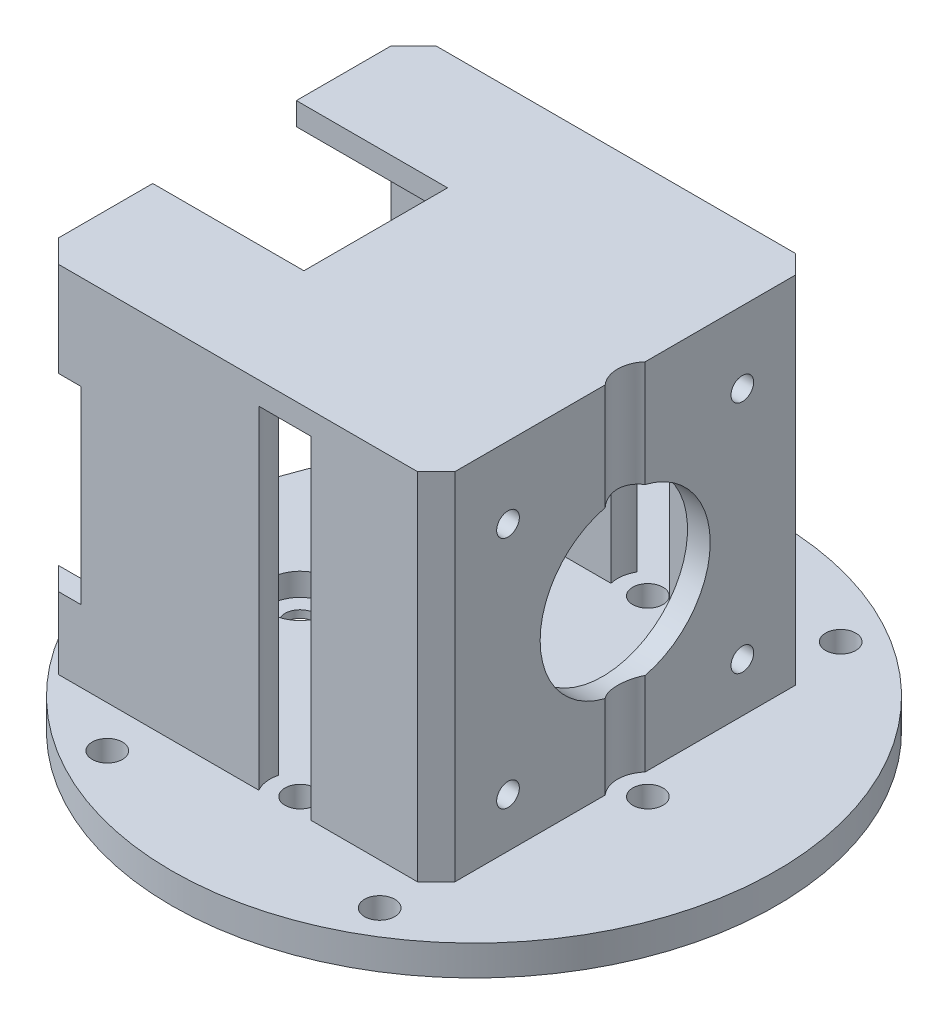
SolidWorks part; units mm, degrees
ref_plane "前视基准面" through (0, 0, 0) normal (0, 0, 1) x (1, 0, 0)
ref_plane "上视基准面" through (0, 0, 0) normal (0, 1, 0) x (1, 0, 0)
ref_plane "右视基准面" through (0, 0, 0) normal (1, 0, 0) x (0, 0, -1)
other "Configuration Table"
sketch "草图1" plane through (0, 0, 0) normal (0, 1, 0) x (1, 0, 0)
  circle A0 centre (0, 0) radius 40
  circle A1 centre (0, 0) radius 23 construction
  circle A2 centre (0, 23) radius 2
  circle A3 centre (23, 0) radius 2
  circle A4 centre (0, -23) radius 2
  circle A5 centre (-23, 0) radius 2
  point P15 (0, 0)
  dimension "D1" = 80
  dimension "D2" = 46
  dimension "D3" = 4
  dimension "D4" = 4
extrude "凸台-拉伸1" add sketch "草图1" along normal blind 4
sketch "草图2" plane through (0, 4, 0) normal (0, 1, 0) x (1, 0, 0)
  line L0 (-8, 0) -> (0, 0) construction
  line L1 (-33, 22) -> (-3.873, 22)
  line L3 (-33, -22) -> (-3.873, -22)
  line L4 (17, 22) -> (17, -22)
  line L5 (-33, 22) -> (17, -22) construction
  line L6 (-33, -22) -> (17, 22) construction
  line L7 (-33, -22) -> (-30, -25)
  line L8 (-30, -25) -> (-3.4641, -25)
  line L9 (-33, 22) -> (-30, 25)
  line L10 (17, -22) -> (3.873, -22) construction
  line L12 (-30, 25) -> (-3.4641, 25)
  line L14 (-33, 22) -> (-3.873, 22) construction
  line L15 (17.5251, 25) -> (20, 22.5251)
  line L16 (20, 22.5251) -> (20, 2.6458)
  line L17 (20, -22.5251) -> (17.5251, -25)
  line L18 (3.4641, 25) -> (17.5251, 25)
  line L19 (20, -2.6458) -> (20, -22.5251)
  line L20 (3.4641, -25) -> (17.5251, -25)
  line L21 (3.873, 22) -> (17, 22)
  line L22 (3.873, 22) -> (17, 22) construction
  line L23 (3.873, -22) -> (17, -22)
  line L24 (-3.873, -22) -> (-33, -22) construction
  circle A0 centre (-23, 0) radius 4
  arc A1 (20, 2.6458) -> (20, -2.6458) centre (23, 0) ccw
  arc A3 (3.4641, -25) -> (3.873, -22) centre (0, -23) ccw
  arc A4 (-3.4641, 25) -> (-3.873, 22) centre (0, 23) ccw
  arc A5 (3.873, 22) -> (3.4641, 25) centre (0, 23) ccw
  arc A6 (-3.873, -22) -> (-3.4641, -25) centre (0, -23) ccw
  circle A7 centre (23, 0) radius 4
  point P0 (-8, 0)
  dimension "D4" = 8
  dimension "D11" = 8
  dimension "D12" = 8
  dimension "D13" = 8
  dimension "D14" = 135
  dimension "D17" = 8
  dimension "D1" = 44
  dimension "D2" = 50
  dimension "D3" = 8
  dimension "D5" = 50
  dimension "D6" = 45
  dimension "D7" = 135
  dimension "D8" = 3
  dimension "D9" = 3
  dimension "D10" = 3
  dimension "D15" = 3.5
  dimension "D16" = 3.5
extrude "凸台-拉伸2" add sketch "草图2" along normal blind 44 contours L9 L12 A4 L1 | L4 L23 A3 L20 L17 L19 A1 L16 L15 L18 A5 L21 | L3 A6 L8 L7
sketch "草图3" plane through (0, 48, 0) normal (0, 1, 0) x (1, 0, 0)
  line L0 (-3.4641, 25) -> (3.4641, 25)
  line L1 (-3.873, 22) -> (3.873, 22) construction
  line L2 (-3.873, -22) -> (3.873, -22) construction
  line L3 (-33, 22) -> (-3.873, 22)
  line L4 (-3.4641, 25) -> (-30, 25)
  line L5 (-30, 25) -> (-33, 22)
  line L6 (-33, 22) -> (-3.873, 22) construction
  line L7 (-3.4641, 25) -> (-30, 25)
  line L8 (-30, 25) -> (-33, 22)
  line L9 (-33, -22) -> (-30, -25)
  line L10 (-30, -25) -> (-3.4641, -25)
  line L11 (-3.873, -22) -> (-33, -22)
  line L12 (-33, -22) -> (-30, -25)
  line L13 (-30, -25) -> (-3.4641, -25)
  line L14 (-3.873, -22) -> (-33, -22) construction
  line L15 (3.873, 22) -> (17, 22)
  line L16 (17, 22) -> (17, -22)
  line L17 (17, -22) -> (3.873, -22)
  line L18 (3.4641, -25) -> (17.5251, -25)
  line L19 (17.5251, -25) -> (20, -22.5251)
  line L20 (20, -22.5251) -> (20, -2.6458)
  line L21 (20, 2.6458) -> (20, 22.5251)
  line L22 (20, 22.5251) -> (17.5251, 25)
  line L23 (17.5251, 25) -> (3.4641, 25)
  line L24 (3.873, 22) -> (17, 22) construction
  line L25 (17, 22) -> (17, -22) construction
  line L26 (17, -22) -> (3.873, -22) construction
  line L27 (3.4641, -25) -> (17.5251, -25)
  line L28 (17.5251, -25) -> (20, -22.5251)
  line L29 (20, -22.5251) -> (20, -2.6458)
  line L30 (20, 2.6458) -> (20, 22.5251)
  line L31 (20, 22.5251) -> (17.5251, 25)
  line L32 (17.5251, 25) -> (3.4641, 25)
  line L33 (-3.4641, -25) -> (3.4641, -25)
  line L34 (-33, 22) -> (-33, 9.5)
  line L35 (17, 0) -> (-13, 0) construction
  line L36 (-13, 7.5) -> (-13, -7.5)
  line L39 (-33, -9.5) -> (-33, -22)
  line L40 (-13, 7.5) -> (-13, 9.5)
  line L41 (-13, 9.5) -> (-23, 9.5)
  line L43 (-13, -9.5) -> (-23, -9.5)
  line L46 (-13, -7.5) -> (-13, -9.5)
  line L47 (-23, 9.5) -> (-33, 9.5)
  line L48 (-33, -9.5) -> (-23, -9.5)
  arc A1 (-3.4641, 25) -> (-3.873, 22) centre (0, 23) ccw
  arc A3 (-3.873, -22) -> (-3.4641, -25) centre (0, -23) ccw
  arc A5 (3.4641, -25) -> (3.873, -22) centre (0, -23) ccw
  arc A6 (20, 2.6458) -> (20, -2.6458) centre (23, 0) ccw
  arc A7 (3.873, 22) -> (3.4641, 25) centre (0, 23) ccw
  arc A9 (20, 2.6458) -> (20, -2.6458) centre (23, 0) ccw
  dimension "D4" = 30
  dimension "D5" = 15
  dimension "D6" = 19
  dimension "D8" = 10
  dimension "D1" = 0
  dimension "D2" = 0
  dimension "D3" = 0
extrude "凸台-拉伸4" add sketch "草图3" along normal blind 3
sketch "草图5" plane through (17, 0, 0) normal (-1, 0, 0) x (0, 0, 1)
  line L0 (-22, 48) -> (22, 4) construction
  line L1 (22, 48) -> (-22, 4) construction
  line L3 (-15.5, 41.5) -> (15.5, 41.5) construction
  line L4 (-15.5, 41.5) -> (-15.5, 10.5) construction
  line L5 (-15.5, 10.5) -> (15.5, 10.5) construction
  line L6 (15.5, 41.5) -> (15.5, 10.5) construction
  line L7 (-15.5, 41.5) -> (15.5, 10.5) construction
  line L8 (-15.5, 10.5) -> (15.5, 41.5) construction
  circle A0 centre (15.5, 41.5) radius 1.5
  circle A1 centre (-15.5, 41.5) radius 1.5
  circle A2 centre (-15.5, 10.5) radius 1.5
  circle A3 centre (15.5, 10.5) radius 1.5
  circle A4 centre (0, 26) radius 11.25
  point P8 (0, 26)
  dimension "D3" = 3
  dimension "D6" = 22.5
  dimension "D1" = 31
  dimension "D2" = 31
  dimension "D4" = 2
  dimension "D5" = 2
extrude "切除-拉伸1" cut sketch "草图5" against normal through all
sketch "草图6" plane through (0, 0, 25) normal (0, 0, 1) x (1, 0, 0)
  line L0 (-33, 26) -> (20, 26) construction
  line L1 (-33, 48) -> (-33, 4) construction
  line L2 (20, 51) -> (20, 4) construction
  line L3 (-33, 38.5) -> (-33, 13.5)
  line L4 (-33, 38.5) -> (-27, 38.5)
  line L5 (-27, 38.5) -> (-27, 13.5)
  line L6 (-33, 13.5) -> (-27, 13.5)
  point P10 (-27, 26)
  dimension "D1" = 12.5
  dimension "D2" = 6
extrude "切除-拉伸2" cut sketch "草图6" against normal blind 3
sketch "草图8" plane through (0, 4, 0) normal (0, 1, 0) x (1, 0, 0)
  line L0 (0, 0) -> (23, 0) construction
  line L1 (0, 0) -> (18.0143, 30.4969) construction
  line L2 (0, 0) -> (0, 35.42) construction
  circle A0 centre (0, 0) radius 35.42 construction
  circle A1 centre (18.0143, 30.4969) radius 2
  circle A2 centre (18.0143, -30.4969) radius 2
  circle A3 centre (-18.0143, -30.4969) radius 2
  circle A4 centre (-18.0143, 30.4969) radius 2
  dimension "D1" = 70.84
  dimension "D3" = 4
  dimension "D2" = 59.43
extrude "切除-拉伸3" cut sketch "草图8" against normal through all contours A4 | A1 | A2 | A3
sketch "草图9" plane through (0, 4, 0) normal (0, 1, 0) x (1, 0, 0)
  circle A0 centre (-23, 0) radius 4
  dimension "D1" = 8
extrude "切除-拉伸4" cut sketch "草图9" against normal blind 3
